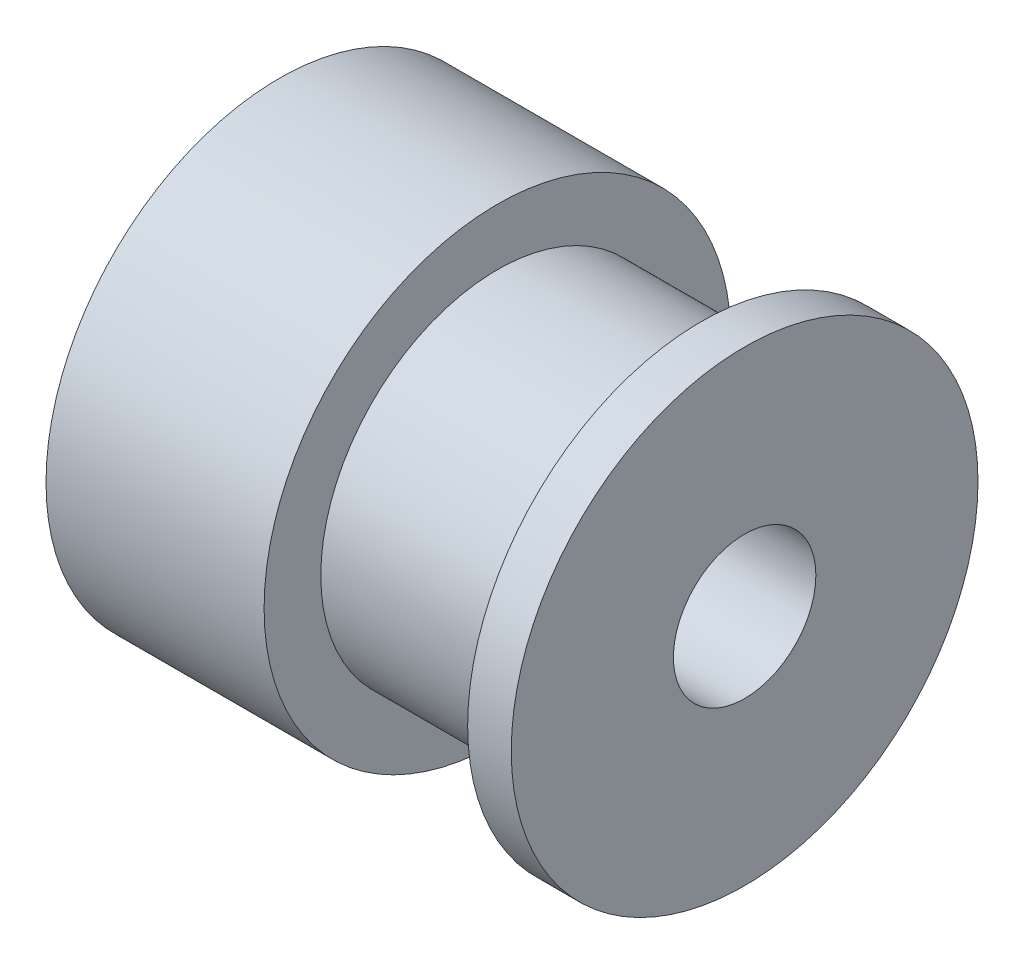
SolidWorks part; units mm, degrees
ref_plane "Front Plane" through (0, 0, 0) normal (0, 0, 1) x (1, 0, 0)
ref_plane "Top Plane" through (0, 0, 0) normal (0, 1, 0) x (1, 0, 0)
ref_plane "Right Plane" through (0, 0, 0) normal (1, 0, 0) x (0, 0, -1)
sketch "Sketch1" plane through (0, 0, 0) normal (1, 0, 0) x (0, 0, -1)
  circle A0 centre (0, 0) radius 8.025
  circle A1 centre (0, 0) radius 2.45
  dimension "D1" = 16.05
  dimension "D2" = 4.9
extrude "Boss-Extrude1" add sketch "Sketch1" along normal blind 16
ref_plane "Plane1" through (7.5, 0, 0) normal (1, 0, 0) x (0, 0, -1)
sketch "Sketch3" plane through (0, 0, 0) normal (0, 0, 1) x (1, 0, 0)
  line L0 (-1.7843, 0) -> (20.0332, 0) construction
  line L1 (7.5, 9.373) -> (7.5, -9.9217) construction
  line L2 (7.5, -8.8275) -> (7.5, 8.8275) construction
  line L3 (16, 8.025) -> (0, 8.025) construction
  line L4 (7.5, 8.025) -> (14.5, 8.025)
  line L5 (7.5, 8.025) -> (7.5, 6.075)
  line L6 (7.5, 6.075) -> (14.5, 6.075)
  line L7 (14.5, 8.025) -> (14.5, 6.075)
  dimension "D1" = 7
  dimension "D2" = 1.95
revolve "Cut-Revolve1" cut sketch "Sketch3" angle 360 about L0
